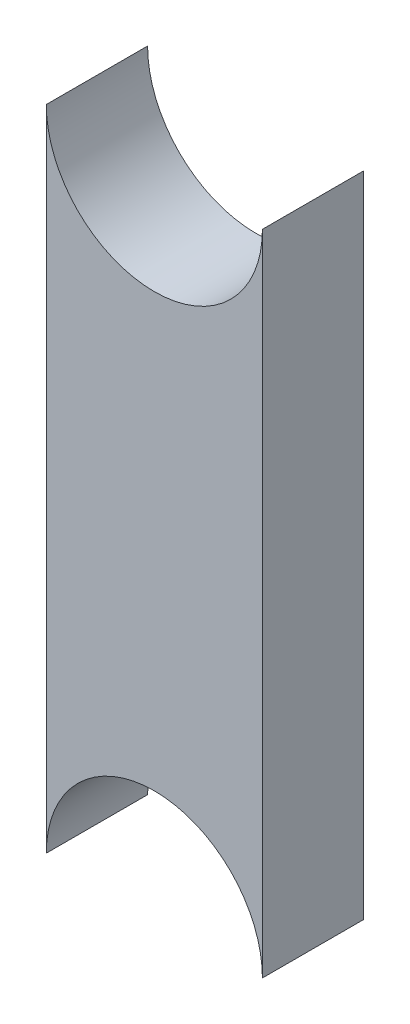
SolidWorks part; units mm, degrees
ref_plane "Front Plane" through (0, 0, 0) normal (0, 0, 1) x (1, 0, 0)
ref_plane "Top Plane" through (0, 0, 0) normal (0, 1, 0) x (1, 0, 0)
ref_plane "Right Plane" through (0, 0, 0) normal (1, 0, 0) x (0, 0, -1)
sketch "Sketch1" plane through (0, 0, 0) normal (0, 0, 1) x (1, 0, 0)
  line L1 (-3.2, 0) -> (-3.2, 19.2)
  line L2 (3.2, 19.2) -> (3.2, 0)
  line L3 (0, -2.75) -> (0, 2.75) construction
  arc A2 (3.2, 0) -> (-3.2, 0) centre (0, 0) ccw
  arc A3 (-3.2, 19.2) -> (3.2, 19.2) centre (0, 19.2) ccw
  dimension "D1" = 6.4
  dimension "D2" = 19.2
extrude "Boss-Extrude3" add sketch "Sketch1" along normal blind 3
equation "\"bScale\"= 8"
equation "\"lScale\"= 8"
equation "\"D1@Sketch1\"=.8*\"bScale\""
equation "\"D2@Sketch1\"=2.4*\"lScale\""
